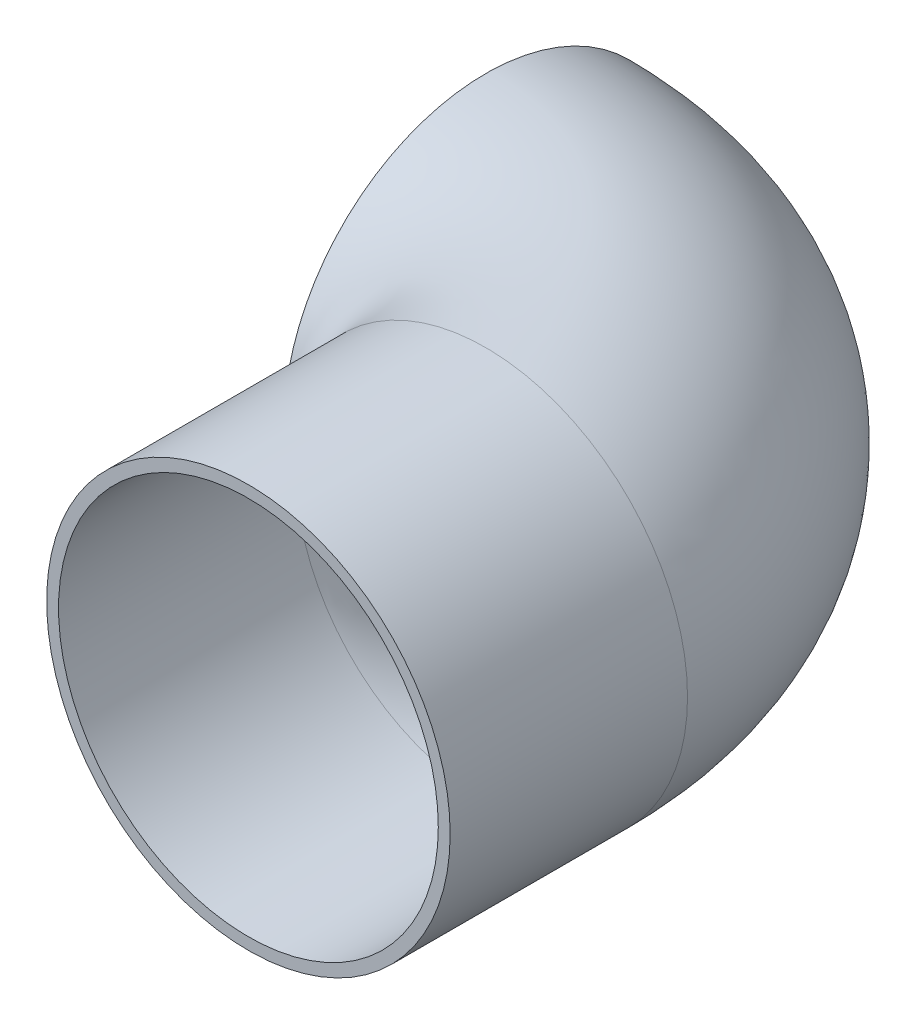
SolidWorks part; units mm, degrees
ref_plane "前视基准面" through (0, 0, 0) normal (0, 0, 1) x (1, 0, 0)
ref_plane "上视基准面" through (0, 0, 0) normal (0, 1, 0) x (1, 0, 0)
ref_plane "右视基准面" through (0, 0, 0) normal (1, 0, 0) x (0, 0, -1)
other "Configuration Table"
sketch "草图2" plane through (0, 0, 0) normal (0, 0, 1) x (1, 0, 0)
  circle A0 centre (0, 0) radius 8.5
  circle A1 centre (0, 0) radius 8
  dimension "D1" = 17
  dimension "D2" = 16
sketch "草图3" plane through (0, 0, 0) normal (0, 1, 0) x (1, 0, 0)
  line L0 (0, 0) -> (0, 10)
  line L1 (-8, 0) -> (8, 0) construction
  arc A0 (0, 10) -> (-10, 20) centre (-10, 10) ccw
  dimension "D1" = 10
sweep "扫描5" add profiles "草图2" path "草图3"
